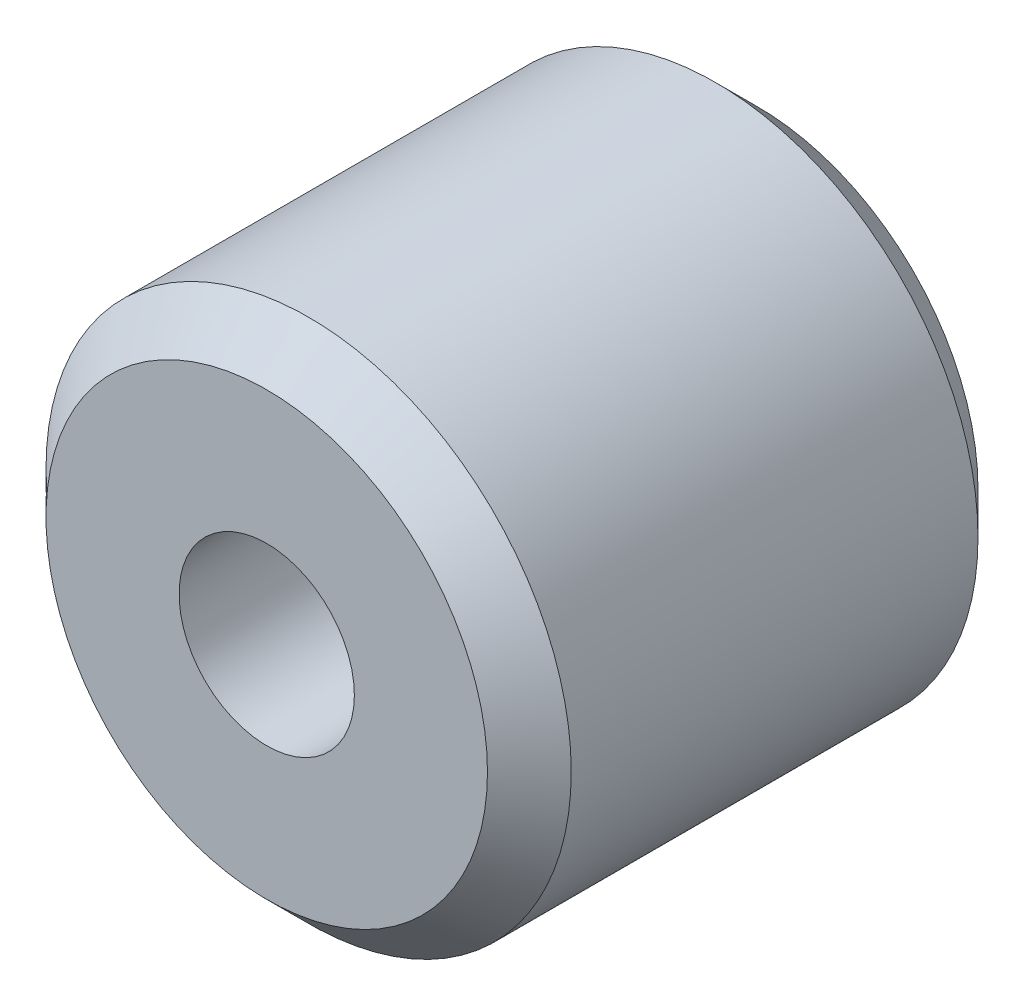
SolidWorks part; units mm, degrees
ref_plane "Front Plane" through (0, 0, 0) normal (0, 0, 1) x (1, 0, 0)
ref_plane "Top Plane" through (0, 0, 0) normal (0, 1, 0) x (1, 0, 0)
ref_plane "Right Plane" through (0, 0, 0) normal (1, 0, 0) x (0, 0, -1)
sketch "Sketch1" plane through (0, 0, 0) normal (0, 0, 1) x (1, 0, 0)
  circle A0 centre (0, 0) radius 4.765
  circle A1 centre (0, 0) radius 1.59
extrude "Boss-Extrude1" add sketch "Sketch1" along normal mid plane 8.9
chamfer "Chamfer1" distance 0.76 angle 45 2 edges at (4.765, 0, -4.45) (4.765, 0, 4.45)
